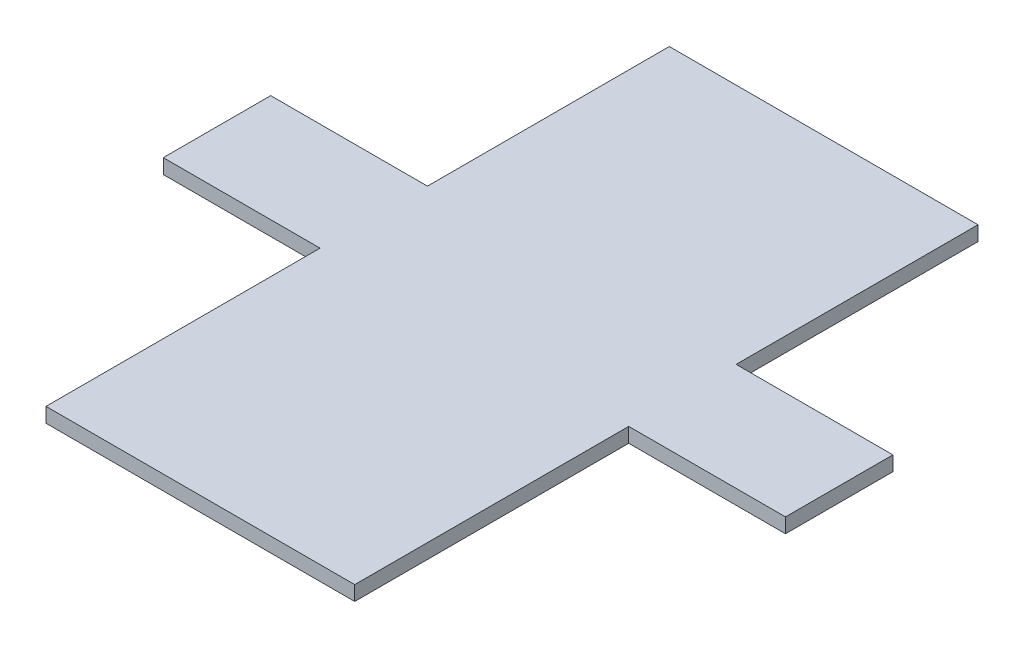
SolidWorks part; units mm, degrees
ref_plane "Plan de face" through (0, 0, 0) normal (0, 0, 1) x (1, 0, 0)
ref_plane "Plan de dessus" through (0, 0, 0) normal (0, 1, 0) x (1, 0, 0)
ref_plane "Plan de droite" through (0, 0, 0) normal (1, 0, 0) x (0, 0, -1)
sketch "Esquisse1" plane through (0, 0, 0) normal (0, 1, 0) x (1, 0, 0)
  line L0 (0, 0) -> (39.43, 0)
  line L3 (0, 79.61) -> (39.43, 79.61)
  line L4 (39.43, 0) -> (39.43, 35)
  line L5 (39.43, 35) -> (59.45, 35)
  line L6 (59.45, 35) -> (59.45, 48.72)
  line L7 (59.45, 48.72) -> (39.43, 48.72)
  line L8 (39.43, 48.72) -> (39.43, 79.61)
  line L9 (0, 48.72) -> (-20.02, 48.72)
  line L10 (-20.02, 48.72) -> (-20.02, 35)
  line L11 (-20.02, 35) -> (0, 35)
  line L12 (0, 48.72) -> (0, 79.61)
  line L13 (0, 35) -> (0, 0)
  line L14 (-20.02, 41.86) -> (59.45, 41.86)
  line L15 (-10.01, 48.72) -> (-10.01, 35)
  line L16 (49.44, 48.72) -> (49.44, 35)
  circle A0 centre (-10.01, 41.86) radius 5.25
  circle A1 centre (49.44, 41.86) radius 5.25
  dimension "D1" = 39.43
  dimension "D2" = 35
  dimension "D3" = 30.89
  dimension "D4" = 20.02
  dimension "D5" = 20.02
extrude "Boss.-Extru.1" add sketch "Esquisse1" along normal blind 1.87 contours L3 L8 L7 L6 L5 L4 L0 L13 L11 L10 L9 L12
